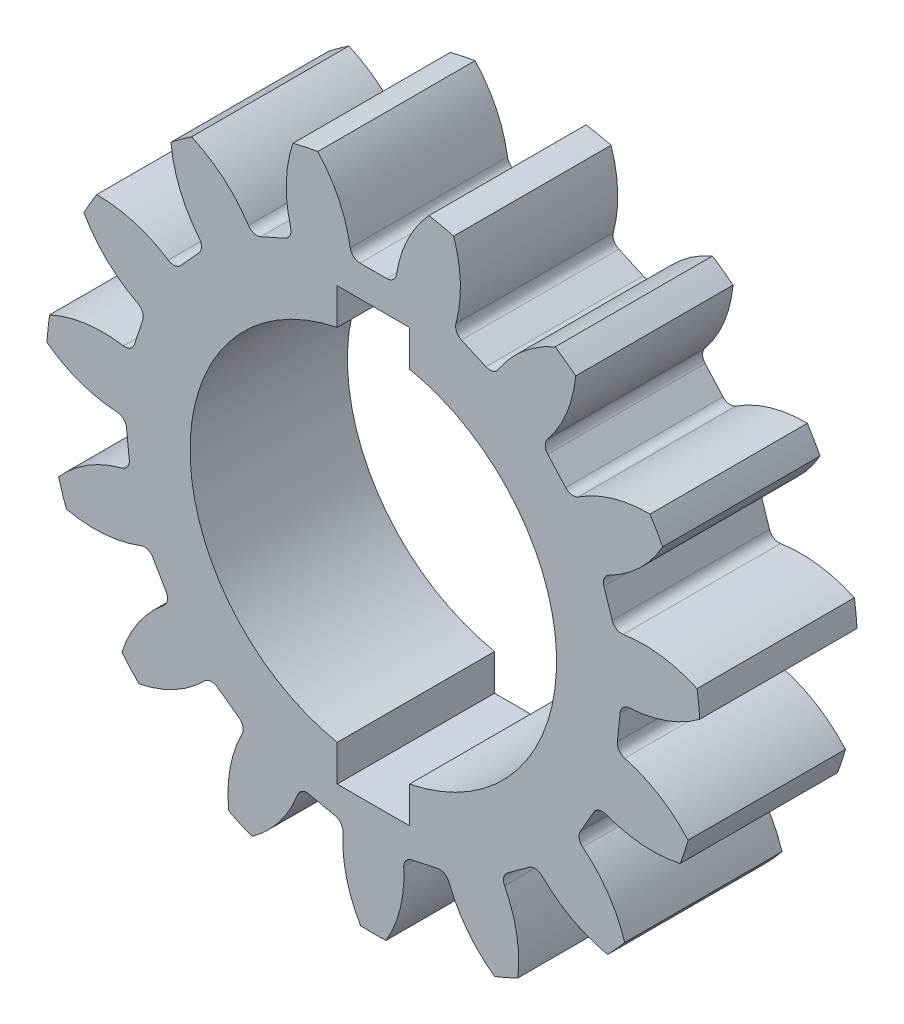
SolidWorks part; units mm, degrees
material "Nickel"
ref_plane "Front Plane" through (0, 0, 0) normal (0, 0, 1) x (1, 0, 0)
ref_plane "Top Plane" through (0, 0, 0) normal (0, 1, 0) x (1, 0, 0)
ref_plane "Right Plane" through (0, 0, 0) normal (1, 0, 0) x (0, 0, -1)
sketch "Sketch1" plane through (0, 0, 0) normal (0, 0, 1) x (1, 0, 0)
  circle A0 centre (0, 0) radius 4.8
  circle A1 centre (0, 0) radius 5.44
  circle A2 centre (0, 0) radius 6.336
  dimension "D1" = 9.6
  dimension "D2" = 10.88
  dimension "D4" = 12.672
  dimension "D3" = 1.536
  dimension "D5" = 0.896
extrude "Boss-Extrude1" add sketch "Sketch1" along normal mid plane 3.048 contours A2
sketch "Sketch3" plane through (0, 0, 0) normal (0, 0, 1) x (1, 0, 0)
  line L0 (0, 0) -> (0, 31.9299) construction
  line L1 (-0.5686, 5.4102) -> (0.5686, 5.4102) construction
  line L2 (-0.4284, 4.7808) -> (0, 0) construction
  line L3 (0, 3.8479) -> (-9.2169, 29.1711) construction
  line L4 (-0.4284, 4.7808) -> (0.4284, 4.7808)
  line L5 (0, 0) -> (7.2755, 34.2287) construction
  line L6 (0.5686, 5.4102) -> (1.6811, 5.1737) construction
  arc A0 (-0.4284, 4.7808) -> (-2.2882, 6.97) centre (-2.9083, 4.5586) ccw
  arc A1 (0.4284, 4.7808) -> (2.2882, 6.97) centre (2.9083, 4.5586) cw
  circle A2 centre (0, 0) radius 4.8 construction
  circle A4 centre (0, 0) radius 5.44 construction
  circle A5 centre (0, 0) radius 7.336
  arc A6 (2.2882, 6.97) -> (-2.2882, 6.97) centre (0, 0) ccw
  dimension "D2" = 20
  dimension "D3" = 12
  dimension "D1" = 1
extrude "Cut-Extrude1" cut sketch "Sketch3" against normal through all both and the other way through all
fillet "Fillet1" radius 0.192 2 edges at (0.4284, 4.7808, 0) (-0.4284, 4.7808, 0)
pattern_circular "CirPattern1" count 15 over 360 about axis through (0, 0, 0) along (0, 0, 1) of "Fillet1", "Cut-Extrude1"
sketch "Sketch4" plane through (0, 0, 1.524) normal (0, 0, 1) x (1, 0, 0)
  circle A0 centre (0, 0) radius 3.55
  point P0 (0, 0)
  dimension "D1" = 7.1
extrude "Cut-Extrude2" cut sketch "Sketch4" against normal through all both and the other way through all
sketch "Sketch5" plane through (0, 0, 1.524) normal (0, 0, 1) x (1, 0, 0)
  circle A0 centre (0, 0) radius 6.336
sketch "Sketch6" plane through (0, 0, 1.524) normal (0, 0, 1) x (1, 0, 0)
  line L0 (0, 0) -> (0, 9.0277) construction
  line L1 (0, 0) -> (6.823, 0) construction
  line L2 (-0.7, 4.1803) -> (0.7, 4.1803)
  line L3 (0.7, 4.1803) -> (0.7, 3.4803)
  line L4 (0.7, 3.4803) -> (-0.7, 3.4803)
  line L5 (-0.7, 4.1803) -> (-0.7, 3.4803)
  line L6 (0.7, -4.1803) -> (0.7, -3.4803)
  line L7 (-0.7, -4.1803) -> (0.7, -4.1803)
  line L8 (-0.7, -4.1803) -> (-0.7, -3.4803)
  line L9 (0.7, -3.4803) -> (-0.7, -3.4803)
  circle A0 centre (0, 0) radius 3.55 construction
  point P9 (0, 3.4803)
  point P10 (0, 4.1803)
  point P14 (0, 0)
  dimension "D1" = 0.7
  dimension "D2" = 0.7
extrude "Cut-Extrude3" cut sketch "Sketch6" against normal through all
equation "\"module\" = 0.64mm"
equation "\"number of teeth\"= 15"
equation "\"D1@Sketch1\"=\"module\"*\"number of teeth\""
equation "\"D2@Sketch1\"=(\"number of teeth\"+2)*(\"module\")"
equation "\"D3@Sketch1\"=\"module\"*if(\"module\"=>1.25,2.25,2.4)"
equation "\"D3@Sketch3\"=180/\"number of teeth\""
equation "\"D1@Fillet1\"=.3*\"module\""
equation "\"D1@CirPattern1\"=\"number of teeth\""
